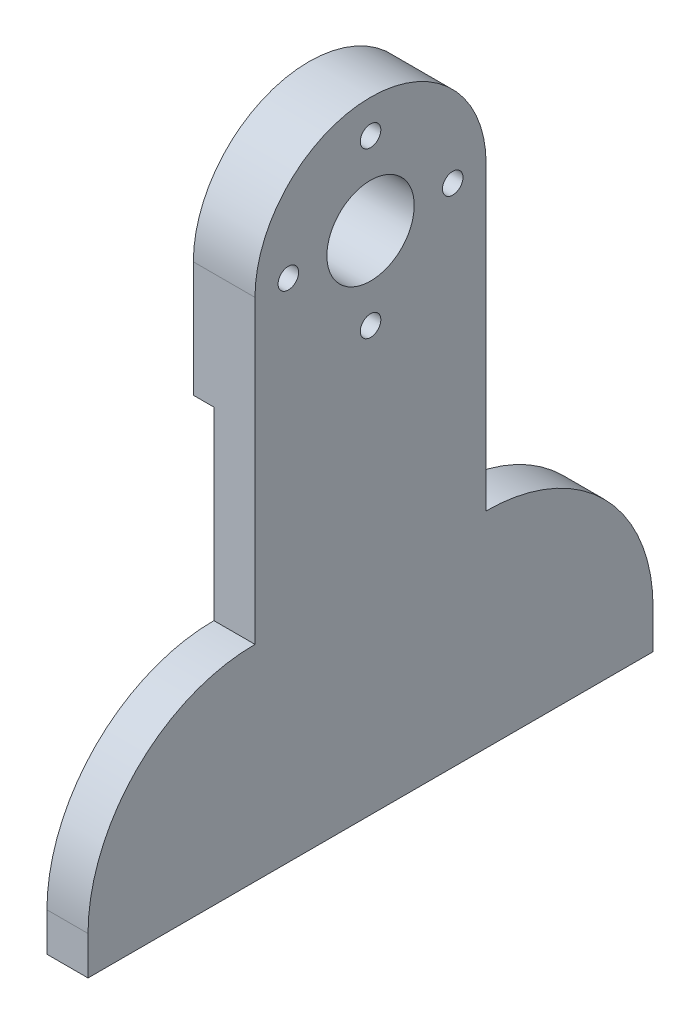
SolidWorks part; units mm, degrees
ref_plane "Front Plane" through (0, 0, 0) normal (0, 0, 1) x (1, 0, 0)
ref_plane "Top Plane" through (0, 0, 0) normal (0, 1, 0) x (1, 0, 0)
ref_plane "Right Plane" through (0, 0, 0) normal (1, 0, 0) x (0, 0, -1)
sketch "Sketch1" plane through (0, 0, 0) normal (0, 0, 1) x (1, 0, 0)
  line L1 (-25, 0) -> (25, 0)
  line L2 (-25, 0) -> (-25, -170)
  line L3 (-25, -170) -> (25, -170)
  line L4 (25, 0) -> (25, -170)
  dimension "D1" = 170
  dimension "D2" = 50
extrude "Boss-Extrude1" add sketch "Sketch1" against normal blind 55
sketch "Sketch2" plane through (0, 0, 0) normal (0, 0, 1) x (1, 0, 0)
  line L0 (25, 0) -> (-25, 0) construction
  line L1 (-17, 0) -> (17, 0)
  line L2 (-17, 0) -> (-17, -27)
  line L3 (-17, -27) -> (17, -27)
  line L4 (17, 0) -> (17, -27)
  line L5 (-25, 0) -> (-25, -170) construction
  dimension "D1" = 8
  dimension "D2" = 34
  dimension "D3" = 27
extrude "Cut-Extrude1" cut sketch "Sketch2" against normal through all
sketch "Sketch3" plane through (25, 0, 0) normal (1, 0, 0) x (0, 0, -1)
  line L0 (0, -170) -> (0, 0) construction
  line L1 (55, -27) -> (0, -27)
  line L2 (55, -27) -> (55, -24)
  line L3 (55, -24) -> (0, -24)
  line L4 (0, -27) -> (0, -24)
  line L5 (55, -170) -> (55, 0) construction
  line L7 (0, 0) -> (10, 0)
  line L8 (0, 0) -> (0, -24)
  line L9 (0, -24) -> (10, -24)
  line L10 (10, 0) -> (10, -24)
  line L11 (55, 0) -> (45, 0)
  line L12 (55, 0) -> (55, -24)
  line L13 (55, -24) -> (45, -24)
  line L14 (45, 0) -> (45, -24)
  circle A0 centre (27.5, -12.75) radius 10.25
  circle A1 centre (27.5, -12.75) radius 4.25
  circle A2 centre (27.5, -12.75) radius 8
  circle A3 centre (27.5, -4.75) radius 1
  circle A4 centre (35.5, -12.75) radius 1
  circle A5 centre (27.5, -20.75) radius 1
  circle A6 centre (19.5, -12.75) radius 1
  point P32 (27.5, -12.75)
  line M7 (0, 0) -> (0, -170)
  line M9 (55, -170) -> (55, 0)
  line M10 (55, 0) -> (0, 0)
  dimension "D2" = 11.25
  dimension "D3" = 27.5
  dimension "D4" = 20.5
  dimension "D7" = 8.5
  dimension "D8" = 16
  dimension "D9" = 4
  dimension "D1" = 3
  dimension "D5" = 10
  dimension "D6" = 10
extrude "Cut-Extrude2" cut sketch "Sketch3" against normal through all contours L14 L3 M10 M9 | L10 L3 M10 M7 | A2 A6 | A2 A6 | A1 | A2 A5 | A2 A5 | A2 A4 | A2 A4 | A2 A3 | A2 A3
sketch "Sketch4" plane through (0, 0, -10) normal (0, 0, 1) x (1, 0, 0)
  line L0 (-25, -24) -> (-17, -24) construction
  line L1 (-17, 0) -> (-19, 0)
  line L2 (-17, 0) -> (-17, -24)
  line L3 (-17, -24) -> (-19, -24)
  line L4 (-19, 0) -> (-19, -24)
  line L5 (0, 0) -> (0, -13.53) construction
  line L6 (19, 0) -> (19, -24)
  line L7 (17, -24) -> (19, -24)
  line L8 (17, 0) -> (17, -24)
  line L9 (17, 0) -> (19, 0)
  dimension "D1" = 2
extrude "Cut-Extrude3" cut sketch "Sketch4" against normal through all
sketch "Sketch5" plane through (25, 0, 0) normal (1, 0, 0) x (0, 0, -1)
  line L1 (10, 0) -> (45, 0)
  line L2 (10, 0) -> (10, -24)
  line L3 (10, -24) -> (45, -24)
  line L4 (45, 0) -> (45, -24)
  line L5 (38.75, -12.75) -> (38.75, -24)
  line L6 (16.25, -12.75) -> (10, -12.75)
  line L7 (16.25, -12.75) -> (16.25, -24)
  line L8 (16.25, -24) -> (10, -24)
  line L9 (10, -12.75) -> (10, -24)
  line L10 (38.75, -12.75) -> (45, -12.75)
  line L11 (38.75, -12.75) -> (38.75, -24)
  line L12 (38.75, -24) -> (45, -24)
  line L13 (45, -12.75) -> (45, -24)
  circle A0 centre (27.5, -12.75) radius 11.25
  line M8 (45, -24) -> (45, 0)
  line M9 (45, 0) -> (10, 0)
  line M10 (10, 0) -> (10, -24)
  dimension "D1" = 22.5
extrude "Cut-Extrude4" cut sketch "Sketch5" against normal through all contours A0 L10 L4 L6 M9 M10 | L7 L6 L2 L3 | L10 L5 L3 M8
sketch "Sketch6" plane through (0, 0, 0) normal (0, 0, 1) x (1, 0, 0)
  line L1 (-19, -24) -> (19, -24)
  line L2 (-19, -24) -> (-19, -34)
  line L3 (-19, -34) -> (19, -34)
  line L4 (19, -24) -> (19, -34)
  dimension "D1" = 10
extrude "Cut-Extrude5" cut sketch "Sketch6" against normal through all
sketch "Sketch8" plane through (25, 0, 0) normal (1, 0, 0) x (0, 0, -1)
  line L0 (55, -170) -> (55, -24) construction
  line L1 (0, -170) -> (0, -24) construction
  line L2 (41.75, -132.5) -> (13.25, -132.5)
  line L3 (27.5, -132.5) -> (27.5, -179)
  line L4 (41.75, -179) -> (13.25, -179)
  line L5 (13.25, -132.5) -> (13.25, -179)
  line L7 (41.75, -132.5) -> (41.75, -179)
  line L11 (27.5, -167.75) -> (55, -167.75)
  line L12 (27.5, -167.75) -> (27.5, -170)
  line L13 (27.5, -170) -> (55, -170)
  line L14 (55, -167.75) -> (55, -170)
  line L16 (27.5, -167.75) -> (0, -167.75)
  line L17 (27.5, -167.75) -> (27.5, -170)
  line L18 (27.5, -170) -> (0, -170)
  line L19 (0, -167.75) -> (0, -170)
  circle A0 centre (27.5, -167.75) radius 10.25
  circle A1 centre (27.5, -12.75) radius 10.25
  line M4 (0, -24) -> (0, -170)
  line M5 (0, -170) -> (55, -170)
  line M6 (55, -170) -> (55, -24)
  dimension "D1" = 27.5
  dimension "D2" = 20.5
  dimension "D3" = 155
  dimension "D4" = 14.25
  dimension "D5" = 11.25
  dimension "D6" = 46.5
  dimension "D7" = 13.25
extrude "Cut-Extrude7" cut sketch "Sketch8" against normal through all contours A0 L3 L2 L5 L16 | A0 L11 L7 L2 L3 | L11 L7 M5 M6 | L5 L16 M4 M5 | A0 L16 L5 M5 | A0 L13 L7 L11 | L3 A0 L16 | L11 A0 L3 | L16 A0 L18 L3 | A0 L11 L3 M5
sketch "Sketch9" plane through (0, 0, 0) normal (0, 0, 1) x (1, 0, 0)
  line L0 (-25, -167.75) -> (25, -167.75) construction
  line L1 (17, -167.75) -> (-17, -167.75)
  line L2 (17, -167.75) -> (17, -132.5)
  line L3 (17, -132.5) -> (-17, -132.5)
  line L4 (-17, -167.75) -> (-17, -132.5)
  line L5 (-25, -132.5) -> (25, -132.5) construction
  line L7 (-25, -24) -> (-25, -167.75) construction
  line L9 (25, -167.75) -> (25, -24) construction
  dimension "D1" = 8
  dimension "D2" = 8
extrude "Cut-Extrude8" cut sketch "Sketch9" against normal through all
sketch "Sketch11" plane through (25, 0, 0) normal (1, 0, 0) x (0, 0, -1)
  line L0 (27.5, -157.5) -> (27.5, -147.5)
  line L2 (27.5, -147.5) -> (55, -147.5)
  line L3 (27.5, -147.5) -> (27.5, -167.75)
  line L4 (27.5, -167.75) -> (55, -167.75)
  line L5 (55, -147.5) -> (55, -167.75)
  line L6 (27.5, -147.5) -> (0, -147.5)
  line L7 (27.5, -147.5) -> (27.5, -167.75)
  line L8 (27.5, -167.75) -> (0, -167.75)
  line L9 (0, -147.5) -> (0, -167.75)
  circle A0 centre (27.5, -167.75) radius 10.25
  arc A1 (38.75, -12.75) -> (16.25, -12.75) centre (27.5, -12.75) ccw construction
  line M1 (0, -167.75) -> (13.25, -167.75)
  line M2 (13.25, -167.75) -> (13.25, -132.5)
  line M4 (41.75, -132.5) -> (41.75, -167.75)
  line M5 (41.75, -167.75) -> (55, -167.75)
  line M6 (55, -167.75) -> (55, -24)
  line M12 (0, -24) -> (0, -167.75)
  dimension "D1" = 155
  dimension "D2" = 20.5
  dimension "D3" = 10
extrude "Cut-Extrude9" cut sketch "Sketch11" against normal through all contours A0 L0 L6 L8 M2 | A0 L4 L2 L0 M4 | L2 M4 M5 M6 | L6 M2 M12 M1
sketch "Sketch12" plane through (25, 0, 0) normal (1, 0, 0) x (0, 0, -1)
  line L1 (13.25, -132.5) -> (41.75, -132.5)
  line L2 (13.25, -132.5) -> (13.25, -147.5)
  line L3 (13.25, -147.5) -> (41.75, -147.5)
  line L4 (41.75, -132.5) -> (41.75, -147.5)
extrude "Boss-Extrude2" add sketch "Sketch12" against normal blind 8
ref_plane "Plane1" through (0, 0, 0) normal (1, 0, 0) x (0, 0, -1)
mirror "Mirror1" about plane through (0, 0, 0) normal (1, 0, 0) of "Boss-Extrude2"
sketch "Sketch14" plane through (0, 0, 0) normal (0, 0, 1) x (1, 0, 0)
  line L0 (17, -148.55) -> (17, -158.75) construction
  line L1 (-17, -132.5) -> (17, -132.5)
  line L2 (-17, -132.5) -> (-17, -147.5)
  line L3 (-17, -147.5) -> (17, -147.5)
  line L4 (17, -132.5) -> (17, -147.5)
  line L5 (-17, -147.5) -> (17, -147.5)
  line L6 (-17, -147.5) -> (-17, -157.75)
  line L7 (-17, -157.75) -> (17, -157.75)
  line L8 (17, -147.5) -> (17, -157.75)
  line M11 (-17, -147.5) -> (-17, -132.5)
  line M12 (-17, -132.5) -> (17, -132.5)
  line M13 (17, -132.5) -> (17, -147.5)
  dimension "D1" = 10.25
extrude "Boss-Extrude3" add sketch "Sketch14" against normal blind 13.25 contours L3 M11 M13 M12 | L8 L3 L6 L7
ref_plane "Plane2" through (0, 0, -27.5) normal (0, 0, 1) x (1, 0, 0)
mirror "Mirror2" about plane through (0, 0, -27.5) normal (0, 0, 1) of "Boss-Extrude3"
sketch "Sketch16" plane through (25, 0, 0) normal (1, 0, 0) x (0, 0, -1)
  line L0 (41.75, -132.5) -> (13.25, -132.5) construction
  line L1 (13.25, -132.5) -> (13.25, -147.5) construction
  circle A1 centre (16.5, -135.75) radius 2.5
  circle A2 centre (16.5, -135.75) radius 4.5
  circle A3 centre (38.5, -135.75) radius 4.5
  dimension "D1" = 3.25
  dimension "D2" = 3.25
  dimension "D3" = 2
extrude "Cut-Extrude13" cut sketch "Sketch16" against normal blind 8 contours A1 | A2 A1 | A3
mirror "Mirror3" about plane through (0, 0, 0) normal (1, 0, 0) of "Cut-Extrude13"
sketch "Sketch17" plane through (25, 0, 0) normal (1, 0, 0) x (0, 0, -1)
  line L0 (55, -147.5) -> (55, -24) construction
  line L1 (38.75, -24) -> (55, -24)
  line L2 (38.75, -24) -> (38.75, -42)
  line L3 (38.75, -42) -> (55, -42)
  line L4 (55, -24) -> (55, -42)
  line L5 (0, -147.5) -> (0, -24) construction
  line L6 (16.25, -24) -> (0, -24)
  line L7 (16.25, -24) -> (16.25, -42)
  line L8 (16.25, -42) -> (0, -42)
  line L9 (0, -24) -> (0, -42)
  dimension "D1" = 18
  dimension "D2" = 18
extrude "Cut-Extrude14" cut sketch "Sketch17" against normal through all
sketch "Sketch18" plane through (25, 0, 0) normal (1, 0, 0) x (0, 0, -1)
  line L9 (0, -147.5) -> (0, -42) construction
  line L18 (16.25, -42) -> (0, -42)
  line L19 (16.25, -42) -> (16.25, -58.25)
  line L20 (16.25, -58.25) -> (0, -58.25)
  line L21 (0, -42) -> (0, -58.25)
  line L22 (55, -147.5) -> (55, -42) construction
  line L23 (38.75, -42) -> (55, -42)
  line L24 (38.75, -42) -> (38.75, -58.25)
  line L25 (38.75, -58.25) -> (55, -58.25)
  line L26 (55, -42) -> (55, -58.25)
  circle A2 centre (16.25, -58.25) radius 16.25
  circle A3 centre (38.75, -58.25) radius 16.25
  line M9 (55, -42) -> (38.75, -42)
  line M13 (16.25, -42) -> (0, -42)
  line M14 (0, -42) -> (0, -147.5)
  line M16 (55, -147.5) -> (55, -42)
  dimension "D1" = 16.25
  dimension "D2" = 16.25
extrude "Cut-Extrude15" cut sketch "Sketch18" against normal through all contours A2 M13 M14 | A3 M16 M9
sketch "Sketch20" plane through (0, 0, -55) normal (0, 0, -1) x (-1, 0, 0)
  line L2 (21, -52) -> (21, -117)
  line L3 (21, -117) -> (-21, -117)
  line L4 (-21, -52) -> (-21, -117)
  line L5 (25, -58.25) -> (25, -147.5) construction
  line L6 (-25, -147.5) -> (-25, -58.25) construction
  line L7 (17, -157.75) -> (-17, -157.75) construction
  line L8 (21, -117) -> (-21, -117)
  line L9 (21, -117) -> (21, -52)
  line L10 (21, -52) -> (-21, -52)
  line L11 (-21, -117) -> (-21, -52)
  line L13 (21, -52) -> (-21, -52)
  line L14 (21, -52) -> (21, -34)
  line L15 (21, -34) -> (-21, -34)
  line L16 (-21, -52) -> (-21, -34)
  line M4 (25, -58.25) -> (-25, -58.25)
  dimension "D1" = 4
  dimension "D2" = 4
  dimension "D3" = 40.75
  dimension "D4" = 65
  dimension "D5" = 83
extrude "Cut-Extrude18" cut sketch "Sketch20" against normal through all contours L2 L10 L4 M4 | L16 L10 L14 L15 | L4 L3 L2 M4
sketch "Sketch22" plane through (-25, 0, 0) normal (-1, 0, 0) x (0, 0, 1)
  circle A0 centre (-38.5, -135.75) radius 4.5
  circle A1 centre (-38.5, -135.75) radius 1.45
  circle A2 centre (-16.5, -135.75) radius 4.5
  circle A3 centre (-16.5, -135.75) radius 1.45
  dimension "D1" = 2.9
extrude "Boss-Extrude4" add sketch "Sketch22" against normal blind 8
mirror "Mirror4" about plane through (0, 0, 0) normal (1, 0, 0) of "Boss-Extrude4"
sketch "Sketch23" plane through (0, 0, -38.75) normal (0, 0, -1) x (-1, 0, 0)
  line L0 (-19, -12.75) -> (-19, -34) construction
  line L1 (-21, -34) -> (-19, -34)
  line L2 (-21, -34) -> (-21, -24)
  line L3 (-21, -24) -> (-19, -24)
  line L4 (-19, -34) -> (-19, -24)
  line L5 (19, -34) -> (19, -12.75) construction
  line L6 (21, -34) -> (19, -34)
  line L7 (21, -34) -> (21, -24)
  line L8 (21, -24) -> (19, -24)
  line L9 (19, -34) -> (19, -24)
  dimension "D1" = 10
  dimension "D2" = 10
extrude "Cut-Extrude19" cut sketch "Sketch23" against normal through all
fillet "Fillet1" radius 10 2 edges at (0, -157.75, 0) (0, -157.75, -55)
sketch "Sketch24" plane through (-25, 0, 0) normal (-1, 0, 0) x (0, 0, 1)
  line L0 (-55, -58.25) -> (-55, -147.5) construction
  line L1 (0, -117) -> (-55, -117)
  line L2 (0, -117) -> (0, -62)
  line L3 (0, -62) -> (-55, -62)
  line L4 (-55, -117) -> (-55, -62)
  dimension "D1" = 55
extrude "Cut-Extrude20" cut sketch "Sketch24" against normal through all
sketch "Sketch25" plane through (-25, 0, 0) normal (-1, 0, 0) x (0, 0, 1)
  line L1 (-72.0771, -91.4572) -> (13.7751, -91.4572)
  line L2 (-72.0771, -91.4572) -> (-72.0771, -167.6785)
  line L3 (-72.0771, -167.6785) -> (13.7751, -167.6785)
  line L4 (13.7751, -91.4572) -> (13.7751, -167.6785)
extrude "Cut-Extrude21" cut sketch "Sketch25" against normal through all
sketch "Sketch26" plane through (0, 0, 0) normal (0, 0, 1) x (1, 0, 0)
  line L1 (-35.9246, 3.2581) -> (-2.9128, 3.2581)
  line L2 (-35.9246, 3.2581) -> (-35.9246, -65.416)
  line L3 (-35.9246, -65.416) -> (-2.9128, -65.416)
  line L4 (-2.9128, 3.2581) -> (-2.9128, -65.416)
extrude "Cut-Extrude22" cut sketch "Sketch26" against normal through all
